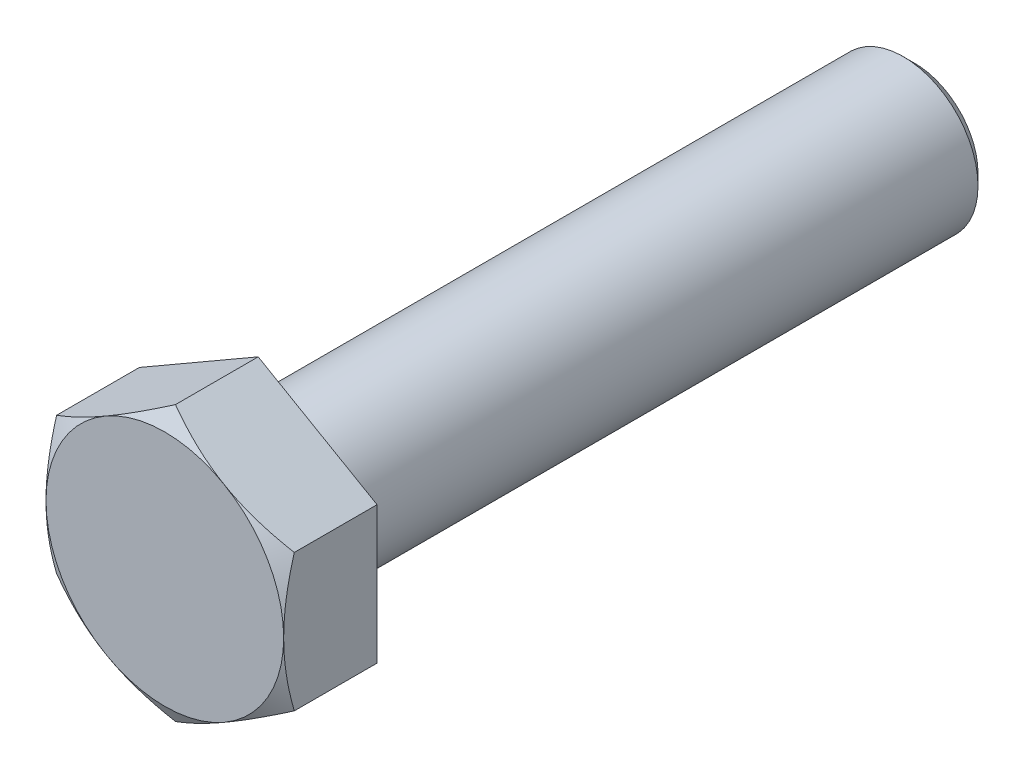
SolidWorks part; units mm, degrees
ref_plane "Front Plane" through (0, 0, 0) normal (0, 0, 1) x (1, 0, 0)
ref_plane "Top Plane" through (0, 0, 0) normal (0, 1, 0) x (1, 0, 0)
ref_plane "Right Plane" through (0, 0, 0) normal (1, 0, 0) x (0, 0, -1)
sketch "Sketch1" plane through (0, 0, 0) normal (0, 0, 1) x (1, 0, 0)
  line L0 (0, 0) -> (0, 7.3497) construction
  line L2 (0, 7.3497) -> (-6.365, 3.6748)
  line L3 (-6.365, 3.6748) -> (-6.365, -3.6748)
  line L4 (-6.365, -3.6748) -> (0, -7.3497)
  line L5 (0, -7.3497) -> (6.365, -3.6748)
  line L6 (6.365, -3.6748) -> (6.365, 3.6748)
  line L7 (6.365, 3.6748) -> (0, 7.3497)
  circle A0 centre (0, 0) radius 6.365 construction
  dimension "HEX" = 12.73
extrude "Boss-Extrude1" add sketch "Sketch1" along normal blind 5.15
sketch "Sketch2" plane through (0, 0, 0) normal (1, 0, 0) x (0, 0, -1)
  line L0 (0, 0) -> (35, 0) construction
  line L1 (0, 0) -> (0, 4.6)
  line L4 (34.4, 4) -> (35, 3.4)
  line L7 (35, 3.4) -> (35, 0)
  line L8 (35, 0) -> (0, 0)
  line L9 (34.4, 4) -> (0.6, 4)
  arc A3 (0.6, 4) -> (0, 4.6) centre (0.6, 4.6) cw
  dimension "LENGTH" = 35
  dimension "WIDTH2" = 6.8
  dimension "WIDTH1" = 8
  dimension "D5" = 45
  dimension "DA" = 9.2
revolve "Revolve1" add sketch "Sketch2" angle 360 about L0
cosmetic thread "Cosmetic Thread1" parameters "D1"=46.25, "D2"=8
sketch "Sketch3" plane through (0, 0, 0) normal (1, 0, 0) x (0, 0, -1)
  line L0 (-12.2049, 0) -> (129.7862, 0) construction
  line L1 (-5.15, 7.3497) -> (-4.5815, 7.3497)
  line L2 (-0.15, 7.3497) -> (-0.15, 5.8866)
  line L3 (-4.5815, 7.3497) -> (-5.15, 6.365)
  line L4 (-0.15, 5.8866) -> (0, 5.8)
  line L5 (-5.15, 6.365) -> (-5.15, 7.3497)
  line L6 (0, -3.6748) -> (0, 3.6748) construction
  line L7 (-5.15, 7.3497) -> (0, 7.3497) construction
  line L8 (-5.15, 3.6748) -> (-5.15, 7.3497) construction
  line L10 (0, 5.8) -> (0, 7.3497)
  line L11 (0, 7.3497) -> (-0.15, 7.3497)
  dimension "D1" = 30
  dimension "SAME AS HEX" = 12.73
  dimension "D3" = 30
  dimension "C" = 0.15
  dimension "DW" = 11.6
revolve "Cut-Revolve1" cut sketch "Sketch3" angle 360 about L0
